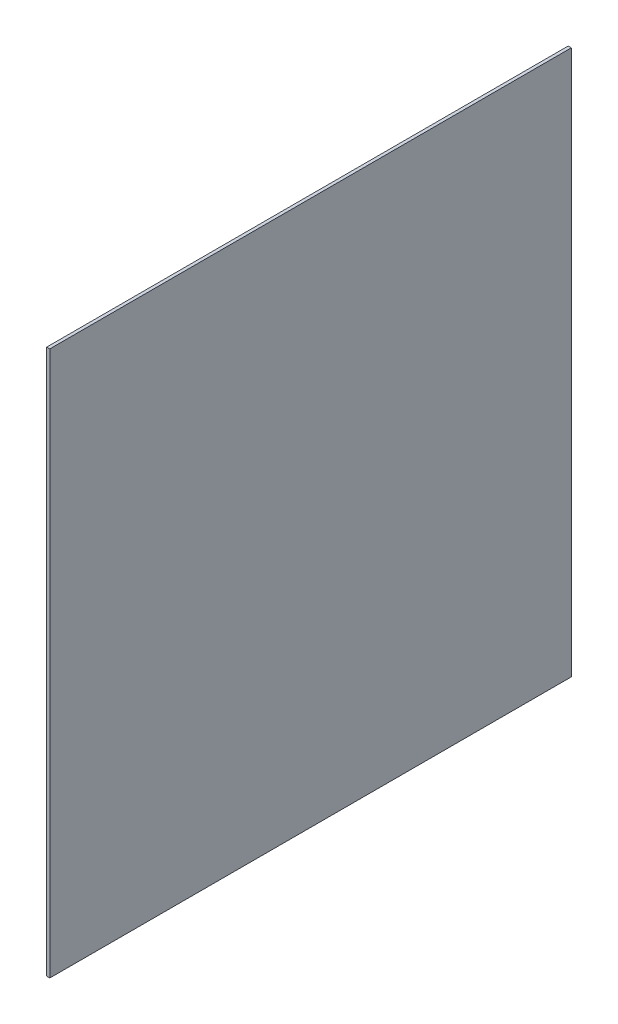
SolidWorks part; units mm, degrees
ref_plane "前视基准面" through (0, 0, 0) normal (0, 0, 1) x (1, 0, 0)
ref_plane "上视基准面" through (0, 0, 0) normal (0, 1, 0) x (1, 0, 0)
ref_plane "右视基准面" through (0, 0, 0) normal (1, 0, 0) x (0, 0, -1)
sketch "草图1" plane through (0, 0, 0) normal (1, 0, 0) x (0, 0, -1)
  line L1 (0, 0) -> (335, 0)
  line L2 (0, 0) -> (0, 350)
  line L3 (0, 350) -> (335, 350)
  line L4 (335, 0) -> (335, 350)
  dimension "D1" = 350
  dimension "D2" = 335
extrude "凸台-拉伸1" add sketch "草图1" along normal blind 2
